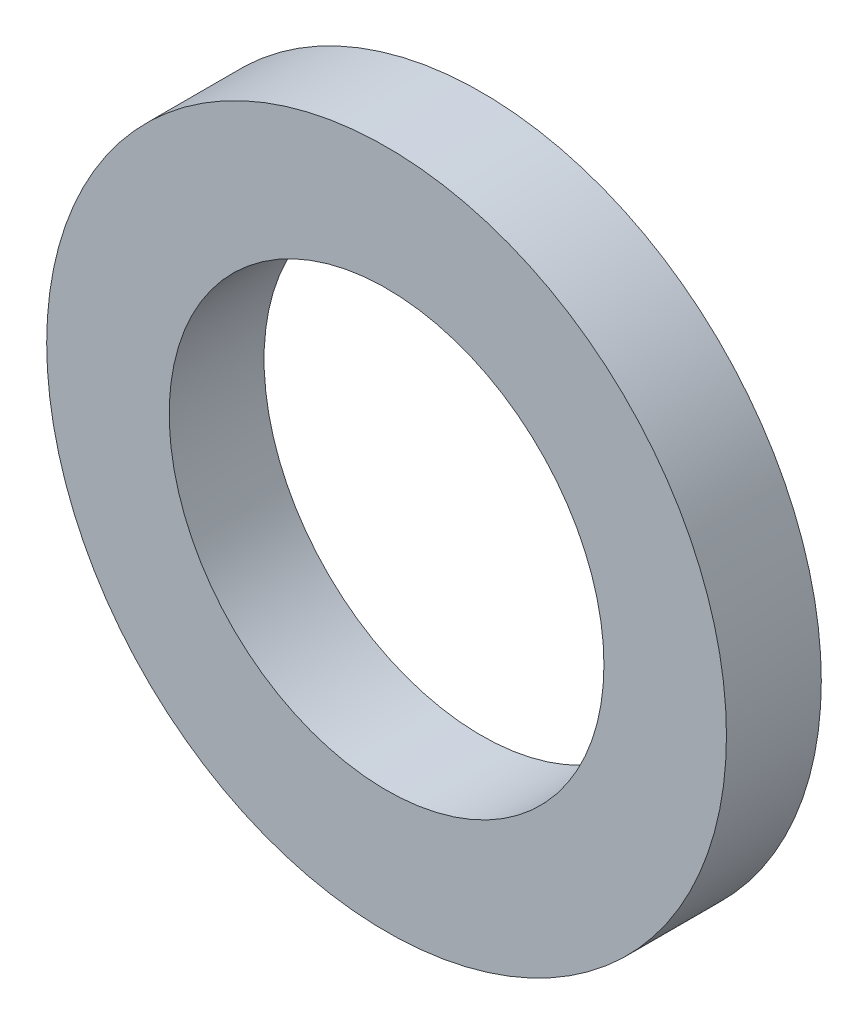
SolidWorks part; units mm, degrees
ref_plane "Front Plane" through (0, 0, 0) normal (0, 0, 1) x (1, 0, 0)
ref_plane "Top Plane" through (0, 0, 0) normal (0, 1, 0) x (1, 0, 0)
ref_plane "Right Plane" through (0, 0, 0) normal (1, 0, 0) x (0, 0, -1)
sketch "Sketch1" plane through (0, 0, 0) normal (0, 0, 1) x (1, 0, 0)
  circle A0 centre (0, 0) radius 43
  circle A1 centre (0, 0) radius 27.5
  dimension "D1" = 86
  dimension "D2" = 55
extrude "Boss-Extrude1" add sketch "Sketch1" along normal blind 12 contours A0
